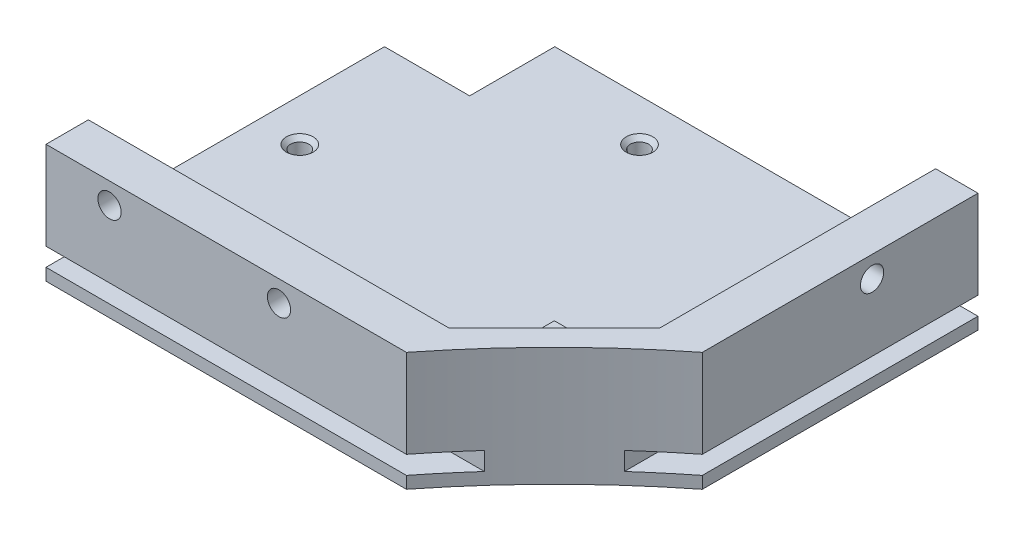
SolidWorks part; units mm, degrees
ref_plane "Front Plane" through (0, 0, 0) normal (0, 0, 1) x (1, 0, 0)
ref_plane "Top Plane" through (0, 0, 0) normal (0, 1, 0) x (1, 0, 0)
ref_plane "Right Plane" through (0, 0, 0) normal (1, 0, 0) x (0, 0, -1)
sketch "Sketch1" plane through (0, 0, 0) normal (0, 1, 0) x (1, 0, 0)
  line L0 (0, 0) -> (0, 650)
  line L1 (0, 650) -> (650, 650)
  line L2 (650, 650) -> (650, 0)
  line L3 (650, 0) -> (0, 0)
  dimension "D1" = 650
  dimension "D2" = 650
extrude "Boss-Extrude1" add sketch "Sketch1" along normal blind 8
sketch "Sketch3" plane through (0, 0, 0) normal (0, 0, 1) x (1, 0, 0)
  line L0 (325, 8) -> (325, 43.7071) construction
  line L1 (0, 8) -> (650, 8) construction
  line L2 (300, 43.7071) -> (350, 43.7071)
  line L3 (300, 43.7071) -> (265, 8)
  line L4 (265, 8) -> (385, 8)
  line L5 (385, 8) -> (350, 43.7071)
  point P7 (325, 43.7071)
  dimension "D1" = 50
  dimension "D2" = 50
  dimension "D3" = 50
  dimension "D4" = 120
extrude "Boss-Extrude2" add sketch "Sketch3" against normal blind 650
sketch "Sketch4" plane through (0, 0, 0) normal (0, 0, 1) x (1, 0, 0)
  line L0 (265, 8) -> (385, 8) construction
  circle A0 centre (325, 22) radius 11
  dimension "D1" = 14
extrude "Cut-Extrude2" cut sketch "Sketch4" against normal through all both and the other way through all
sketch "Sketch2" plane through (0, 8, 0) normal (0, 1, 0) x (1, 0, 0)
  line L0 (0, 650) -> (0, 0) construction
  line L1 (650, 650) -> (385, 650) construction
  circle A0 centre (325, 325) radius 210
  dimension "D3" = 420
  dimension "D1" = 325
  dimension "D2" = 325
extrude "Cut-Extrude1" cut sketch "Sketch2" against normal through all both and the other way through all
sketch "Sketch5" plane through (0, 0, 0) normal (0, 0, 1) x (1, 0, 0)
  line L0 (300, 43.7071) -> (350, 43.7071)
  line L1 (265, 8) -> (385, 8) construction
  line L2 (300, 8) -> (300, 28)
  line L3 (300, 8) -> (350, 8)
  line L4 (350, 8) -> (350, 28)
  line L5 (350, 28) -> (365.3961, 28)
  line L6 (385, 8) -> (350, 43.7071) construction
  line L7 (365.3961, 28) -> (350, 43.7071)
  line L8 (300, 28) -> (284.6039, 28)
  line L9 (300, 43.7071) -> (265, 8) construction
  line L10 (284.6039, 28) -> (300, 43.7071)
extrude "Cut-Extrude3" cut sketch "Sketch5" against normal blind 110 and the other way through all
sketch "Sketch6" plane through (0, 0, -650) normal (0, 0, -1) x (-1, 0, 0)
  line L0 (-265, 8) -> (-385, 8) construction
  line L1 (-350, 43.7071) -> (-300, 43.7071)
  line L2 (-300, 8) -> (-300, 28)
  line L3 (-300, 28) -> (-284.6039, 28)
  line L4 (-300, 43.7071) -> (-265, 8) construction
  line L5 (-284.6039, 28) -> (-300, 43.7071)
  line L6 (-350, 8) -> (-350, 28)
  line L7 (-350, 28) -> (-365.3961, 28)
  line L8 (-365.3961, 28) -> (-350, 43.7071)
  line L9 (-350, 8) -> (-300, 8)
extrude "Cut-Extrude4" cut sketch "Sketch6" against normal blind 110
sketch "Sketch7" plane through (0, 8, 0) normal (0, 1, 0) x (1, 0, 0)
  line L1 (325, 325) -> (325, 455) construction
  line L2 (325, 325) -> (325, 195) construction
  line L3 (325, 325) -> (455, 325) construction
  line L4 (325, 325) -> (195, 325) construction
  line L9 (325, 455) -> (455, 455) construction
  line L10 (455, 455) -> (455, 195) construction
  line L11 (455, 195) -> (195, 195) construction
  line L12 (195, 195) -> (195, 455) construction
  line L13 (195, 455) -> (325, 455) construction
  line L14 (195, 455) -> (195, 489.9242)
  line L15 (195, 489.9242) -> (195, 650)
  line L16 (265, 650) -> (0, 650) construction
  line L17 (195, 455) -> (160.0758, 455)
  line L18 (160.0758, 455) -> (0, 455)
  line L19 (0, 650) -> (0, 0) construction
  line L20 (0, 455) -> (-70.8389, 472.4621)
  line L21 (-70.8389, 472.4621) -> (-70.8389, 686.5445)
  line L22 (-70.8389, 686.5445) -> (167.4782, 686.5445)
  line L23 (167.4782, 686.5445) -> (195, 650)
  arc A0 (265, 526.2461) -> (265, 123.7539) centre (325, 325) ccw construction
  dimension "D1" = 130
  dimension "D2" = 130
  dimension "D3" = 130
  dimension "D4" = 130
extrude "Cut-Extrude5" cut sketch "Sketch7" against normal through all both and the other way through all flip side to cut
sketch "Sketch8" plane through (0, 0, -650) normal (0, 0, -1) x (-1, 0, 0)
  line L0 (-195, 8) -> (-195, 28)
  line L1 (-195, 28) -> (-185, 28)
  line L2 (-185, 28) -> (-185, 17)
  line L3 (-185, 17) -> (-175, 8)
  line L4 (-195, 8) -> (0, 8) construction
  line L5 (-175, 8) -> (-195, 8)
  dimension "D1" = 10
  dimension "D2" = 20
  dimension "D3" = 11
  dimension "D4" = 20
extrude "Boss-Extrude3" add sketch "Sketch8" against normal blind 160.08
sketch "Sketch10" plane through (0, 0, 0) normal (-1, 0, 0) x (0, 0, 1)
  line L0 (-455, 8) -> (-455, 28)
  line L1 (-455, 28) -> (-465, 28)
  line L2 (-465, 28) -> (-465, 17)
  line L3 (-465, 17) -> (-475, 8)
  line L4 (-650, 8) -> (-455, 8) construction
  line L5 (-475, 8) -> (-455, 8)
  dimension "D1" = 10
  dimension "D2" = 20
  dimension "D3" = 11
  dimension "D4" = 20
extrude "Boss-Extrude4" add sketch "Sketch10" against normal blind 160.08
sketch "Sketch21" plane through (0, 0, 0) normal (-1, 0, 0) x (0, 0, 1)
  line L0 (-455, 7.15) -> (-465, 7.15)
  line L1 (-455, 0) -> (-455, 28) construction
  line L2 (-465, 7.15) -> (-465, 2.85)
  line L3 (-465, 2.85) -> (-455, 2.85)
  line L4 (-455, 2.85) -> (-455, 7.15)
  line L5 (-650, 0) -> (-455, 0) construction
  dimension "D1" = 2.85
  dimension "D2" = 4.3
extrude "Cut-Extrude10" cut sketch "Sketch21" against normal through all
sketch "Sketch22" plane through (0, 0, -650) normal (0, 0, -1) x (-1, 0, 0)
  line L0 (-195, 7.15) -> (-185, 7.15)
  line L1 (-195, 0) -> (-195, 28) construction
  line L2 (-185, 7.15) -> (-185, 2.85)
  line L3 (-185, 2.85) -> (-195, 2.85)
  line L4 (-195, 2.85) -> (-195, 7.15)
  line L5 (-195, 0) -> (0, 0) construction
  dimension "D1" = 2.85
  dimension "D2" = 4.3
extrude "Cut-Extrude11" cut sketch "Sketch22" against normal through all
sketch "Sketch12" plane through (0, 8, 0) normal (0, 1, 0) x (1, 0, 0)
  line L0 (0, 0) -> (0, 650) construction
  line L1 (0, 650) -> (650, 650) construction
  line L2 (650, 650) -> (0, 0) construction
  circle A0 centre (325, 325) radius 210
sketch "Sketch23" plane through (0, 0, -489.92) normal (0, 0, 1) x (1, 0, 0)
  line L3 (194.9946, 8) -> (195, 28)
  line L4 (195, 28) -> (160.08, 28)
  line L5 (160.08, 28) -> (160.08, 8)
  line L6 (160.08, 8) -> (194.9946, 8)
extrude "Boss-Extrude5" add sketch "Sketch23" along normal blind 60
extrude "Cut-Extrude6" cut sketch "Sketch12" against normal through all both and the other way through all
sketch "Sketch26" plane through (0, 28, 0) normal (0, 1, 0) x (1, 0, 0)
  line L0 (185, 489.92) -> (160.08, 489.92)
  line L1 (160.08, 489.92) -> (160.08, 465)
  line L2 (160.08, 465) -> (185, 489.92)
extrude "Cut-Extrude14" cut sketch "Sketch26" against normal blind 11
sketch "Sketch27" plane through (185, 0, 0) normal (-1, 0, 0) x (0, 0, 1)
  line L0 (-650, 17) -> (-650, 28) construction
  line L1 (-489.92, 28) -> (-650, 28) construction
  circle A0 centre (-610, 23) radius 2.75
  circle A1 centre (-570, 23) radius 2.75
  circle A2 centre (-530, 23) radius 2.75
  dimension "D1" = 40
  dimension "D7" = 5.5
  dimension "D8" = 5.5
  dimension "D9" = 5.5
  dimension "D2" = 40
  dimension "D3" = 40
  dimension "D4" = 5
  dimension "D5" = 5
  dimension "D6" = 5
extrude "Cut-Extrude15" cut sketch "Sketch27" against normal blind 11
sketch "Sketch28" plane through (0, 0, -465) normal (0, 0, -1) x (-1, 0, 0)
  line L0 (0, 28) -> (0, 17) construction
  line L1 (-160.08, 28) -> (0, 28) construction
  circle A0 centre (-130, 23) radius 2.75
  circle A1 centre (-90, 23) radius 2.75
  circle A2 centre (-40, 23) radius 2.75
  dimension "D1" = 5.5
  dimension "D2" = 5.5
  dimension "D3" = 5.5
  dimension "D4" = 40
  dimension "D5" = 50
  dimension "D6" = 40
  dimension "D7" = 5
  dimension "D8" = 5
  dimension "D9" = 5
extrude "Cut-Extrude16" cut sketch "Sketch28" against normal blind 11
sketch "Sketch29" plane through (0, 8, 0) normal (0, 1, 0) x (1, 0, 0)
  line L0 (0, 650) -> (20, 650)
  line L1 (175, 650) -> (0, 650) construction
  line L2 (20, 650) -> (20, 630)
  line L3 (20, 630) -> (0, 630)
  line L4 (0, 650) -> (0, 475) construction
  line L5 (0, 630) -> (0, 650)
extrude "Cut-Extrude17" cut sketch "Sketch29" against normal blind 10
sketch "Sketch30" plane through (0, 8, 0) normal (0, 1, 0) x (1, 0, 0)
  line L0 (195, 650) -> (195, 555)
  line L1 (195, 489.9242) -> (195, 650) construction
  line L2 (195, 555) -> (0, 555)
  line L3 (0, 630) -> (0, 475) construction
  line L4 (195, 650) -> (0, 650)
  line L5 (0, 650) -> (0, 555)
extrude "Cut-Extrude18" cut sketch "Sketch30" against normal through all both and the other way through all
sketch "Sketch31" plane through (0, 8, 0) normal (0, 1, 0) x (1, 0, 0)
  line L0 (0, 555) -> (75, 555)
  line L1 (175, 555) -> (0, 555) construction
  line L2 (0, 555) -> (0, 455)
  line L3 (0, 455) -> (75, 455)
  line L4 (160.0758, 455) -> (0, 455) construction
  line L5 (75, 455) -> (75, 555)
extrude "Cut-Extrude19" cut sketch "Sketch31" against normal through all both and the other way through all
sketch "Sketch32" plane through (0, 8, 0) normal (0, 1, 0) x (1, 0, 0)
  line L0 (75, 555) -> (95.1, 555)
  line L1 (175, 555) -> (75, 555) construction
  line L2 (95.1, 555) -> (95.1, 534.9)
  line L3 (95.1, 534.9) -> (75, 534.9)
  line L4 (75, 555) -> (75, 475) construction
  line L5 (75, 534.9) -> (75, 555)
  dimension "D1" = 20.1
  dimension "D2" = 20.1
extrude "Cut-Extrude20" cut sketch "Sketch32" against normal blind 10
sketch "Sketch33" plane through (0, 8, 0) normal (0, 1, 0) x (1, 0, 0)
  line L0 (95.1, 534.9) -> (95.1, 555) construction
  line L1 (175, 555) -> (95.1, 555) construction
  line L2 (75, 534.9) -> (75, 475) construction
  line L3 (75, 534.9) -> (95.1, 534.9) construction
  circle A0 centre (85, 504.9) radius 2.15
  circle A1 centre (125.1, 545) radius 2.15
  dimension "D1" = 4.3
  dimension "D2" = 4.3
  dimension "D3" = 30
  dimension "D4" = 10
  dimension "D5" = 10
  dimension "D6" = 30
extrude "Cut-Extrude21" cut sketch "Sketch33" against normal blind 10
chamfer "Chamfer1" distance 1 angle 45 2 edges at (125.1, 8, -542.85) (85, 8, -502.75)
